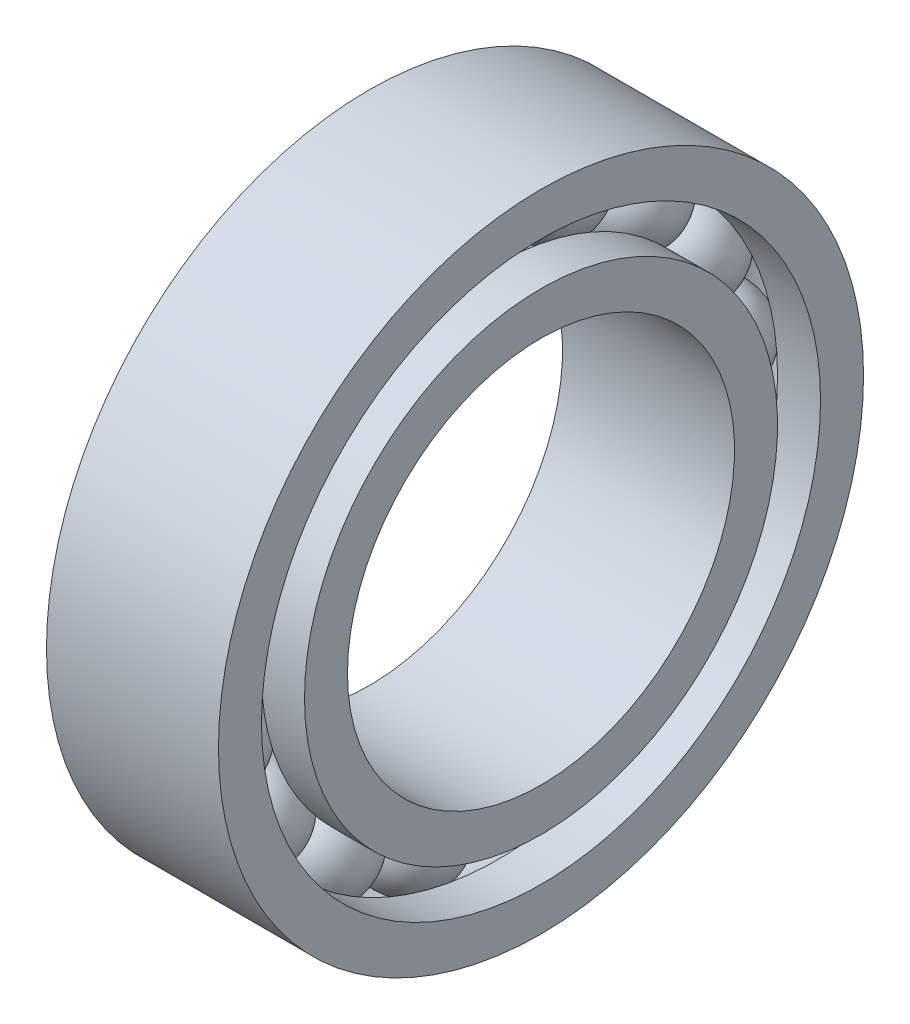
SolidWorks part; units mm, degrees
ref_plane "Piano frontale" through (0, 0, 0) normal (0, 0, 1) x (1, 0, 0)
ref_plane "Piano superiore" through (0, 0, 0) normal (0, 1, 0) x (1, 0, 0)
ref_plane "Piano destro" through (0, 0, 0) normal (1, 0, 0) x (0, 0, -1)
sketch "Schizzo2" plane through (0, 0, 0) normal (0, 0, 1) x (1, 0, 0)
  line L0 (20, 0) -> (-20, 0)
  line L1 (-20, 0) -> (-20, 10)
  line L2 (-20, 10) -> (-10, 10)
  line L3 (0, 0) -> (0, 57497.875) construction
  line L4 (0, 15) -> (50000, 15) construction
  line L5 (20, 10) -> (10, 10)
  line L6 (20, 0) -> (20, 10)
  line L7 (20, 30) -> (20, 20)
  line L8 (20, 20) -> (10, 20)
  line L9 (-20, 20) -> (-10, 20)
  line L10 (-20, 30) -> (-20, 20)
  line L11 (20, 30) -> (-20, 30)
  line L12 (0, -45) -> (50000, -45) construction
  arc A1 (-10, 10) -> (10, 10) centre (0, 15) ccw
  arc A2 (-10, 20) -> (10, 20) centre (0, 15) cw
  point P13 (0, 0)
  point P19 (0, 30)
  dimension "D5" = 60
  dimension "D6" = 11.1803
  dimension "D1" = 10
  dimension "D2" = 20
  dimension "D3" = 10
  dimension "D4" = 15
revolve "Rivoluzione1" add sketch "Schizzo2" angle 360 about L12
sketch "Schizzo4" plane through (0, 0, 0) normal (0, 0, 1) x (1, 0, 0)
  line L0 (0, 0) -> (0, -50000) construction
  line L1 (0, 15) -> (50000, 15) construction
  line L2 (-11, 15) -> (11, 15)
  circle A0 centre (0, 15) radius 11 construction
  arc A1 (-11, 15) -> (11, 15) centre (0, 15) ccw
  dimension "D2" = 22
  dimension "D1" = 15
revolve "Rivoluzione3" add sketch "Schizzo4" angle 360 about L2
sketch "Schizzo8" plane through (0, 0, 0) normal (0, 0, 1) x (1, 0, 0)
  line L0 (0, 0) -> (0, -50000) construction
  line L1 (0, -45) -> (50000, -45) construction
  dimension "D1" = 45
pattern_circular "RipetizioneCircolare2" count 17 over 360 about axis through (0, -45, 0) along (1, 0, 0) of bodies 103
